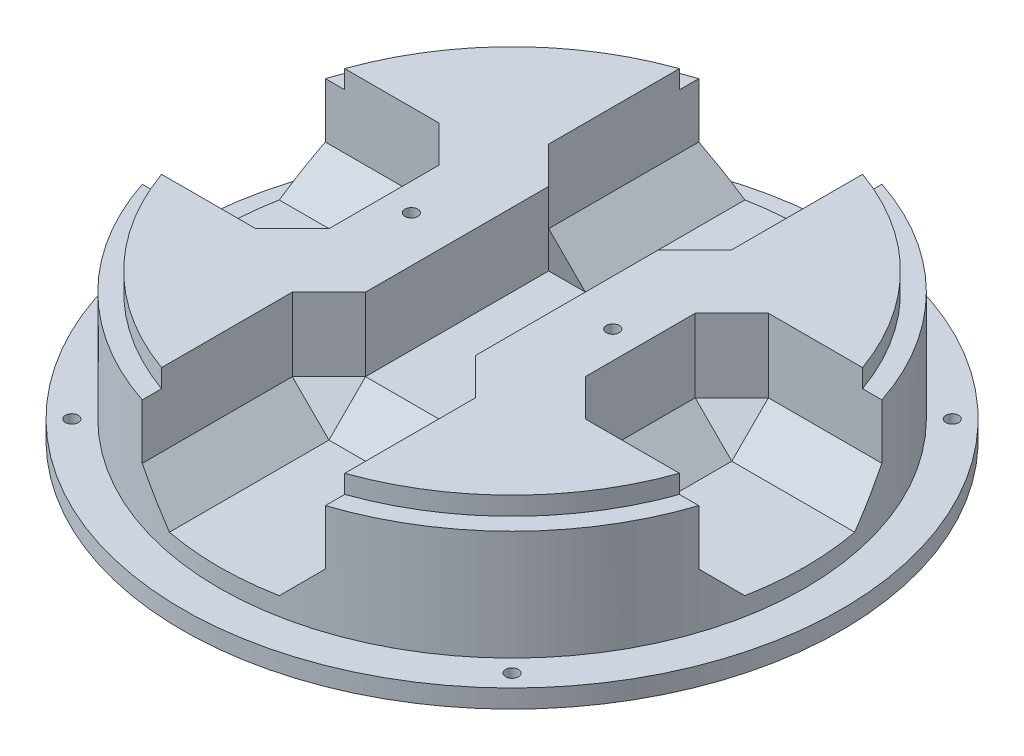
SolidWorks part; units mm, degrees
material "PBT General Purpose"
ref_plane "Front Plane" through (0, 0, 0) normal (0, 0, 1) x (1, 0, 0)
ref_plane "Top Plane" through (0, 0, 0) normal (0, 1, 0) x (1, 0, 0)
ref_plane "Right Plane" through (0, 0, 0) normal (1, 0, 0) x (0, 0, -1)
sketch "Sketch1" plane through (0, 0, 0) normal (0, 1, 0) x (1, 0, 0)
  circle A0 centre (0, 0) radius 80
  dimension "D1" = 160
extrude "Boss-Extrude1" add sketch "Sketch1" along normal blind 30
sketch "Sketch2" plane through (0, 0, 0) normal (0, -1, 0) x (1, 0, 0)
  circle A0 centre (0, 0) radius 90
  dimension "D1" = 180
extrude "Boss-Extrude2" add sketch "Sketch2" along normal blind 5
sketch "Sketch6" plane through (0, 30, 0) normal (0, 1, 0) x (1, 0, 0)
  circle A0 centre (0, 0) radius 75
  dimension "D1" = 150
extrude "Boss-Extrude3" add sketch "Sketch6" along normal blind 5
hole_wizard "Ø3.5 (3.5) Diameter Hole1" positions "Sketch5" profile "Sketch4" hole size "Ø3.5" standard "ISO"
sketch "Sketch5" plane through (-12.746, 35, -7.8689) normal (0, 1, 0) x (1, 0, 0)
  line L0 (-14.754, -7.8689) -> (40.246, -7.8689) construction
  point P1 (-14.754, -7.8689)
  point P2 (40.246, -7.8689)
  dimension "D1" = 55
sketch "Sketch4" plane through (-27.5, 35, 0) normal (1, 0, 0) x (0, 0, 1)
  line L0 (0, 0) -> (0, 11.0515)
  line L1 (0, 11.0515) -> (1.75, 10)
  line L2 (1.75, 10) -> (1.75, 0)
  line L5 (1.75, 0) -> (0, 0)
  line L10 (0, 11.0515) -> (-1.75, 10) construction
  line L11 (0, -6.35) -> (0, 107.95) construction
  dimension "Hole Dia." = 3.5
  dimension "Hole Depth" = 10
  dimension "Drill Angle" = 118
sketch "Sketch7" plane through (0, 35, 0) normal (0, 1, 0) x (1, 0, 0)
  line L0 (0, 25) -> (0, -25) construction
  line L1 (-25, 135) -> (25, 135)
  line L2 (-25, 135) -> (-25, 25)
  line L3 (-25, 25) -> (25, 25)
  line L4 (25, 135) -> (25, 25)
  line L5 (-25, 135) -> (25, 25) construction
  line L6 (-25, 25) -> (25, 135) construction
  line L7 (-25, -25) -> (25, -25)
  line L8 (-25, -25) -> (-25, -135)
  line L9 (-25, -135) -> (25, -135)
  line L10 (25, -25) -> (25, -135)
  line L11 (-25, -25) -> (25, -135) construction
  line L12 (-25, -135) -> (25, -25) construction
  circle A0 centre (0, 0) radius 80 construction
  circle A1 centre (0, 0) radius 80 construction
  point P0 (0, 80)
  point P9 (0, -80)
  dimension "D1" = 50
  dimension "D2" = 50
extrude "Cut-Extrude1" cut sketch "Sketch7" against normal blind 30
chamfer "Chamfer1" distance 10 angle 45 10 edges at (-25, 5, -50.4967) (25, 5, -50.4967) (25, 20, -25) (-25, 20, -25) (0, 5, -25) (-25, 5, 50.4967) (25, 5, 50.4967) (25, 20, 25) (-25, 20, 25) (0, 5, 25)
sketch "Sketch8" plane through (0, 35, 0) normal (0, 1, 0) x (1, 0, 0)
  line L1 (15, 25) -> (-15, 25)
  line L2 (15, 25) -> (15, -25)
  line L3 (15, -25) -> (-15, -25)
  line L4 (-15, 25) -> (-15, -25)
  line L5 (15, 25) -> (-15, -25) construction
  line L6 (15, -25) -> (-15, 25) construction
  point P0 (0, 0)
extrude "Cut-Extrude2" cut sketch "Sketch8" against normal blind 20
hole_wizard "Ø3.5 (3.5) Diameter Hole2" positions "Sketch10" profile "Sketch9" hole size "Ø3.5" standard "ISO"
sketch "Sketch10" plane through (0, 0, 0) normal (0, 1, 0) x (1, 0, 0)
  line L1 (-60.1041, 60.1041) -> (60.1041, 60.1041)
  line L2 (-60.1041, 60.1041) -> (-60.1041, -60.1041)
  line L3 (-60.1041, -60.1041) -> (60.1041, -60.1041)
  line L4 (60.1041, 60.1041) -> (60.1041, -60.1041)
  line L5 (-60.1041, 60.1041) -> (60.1041, -60.1041) construction
  line L6 (-60.1041, -60.1041) -> (60.1041, 60.1041) construction
  point P1 (0, 0)
  point P2 (60.1041, -60.1041)
  point P99 (-60.1041, 60.1041)
  point P100 (-60.1041, -60.1041)
  point P101 (60.1041, 60.1041)
  dimension "D1" = 170
sketch "Sketch9" plane through (0, 0, 0) normal (1, 0, 0) x (0, 0, 1)
  line L0 (0, 0) -> (0, 11.0515)
  line L1 (0, 11.0515) -> (1.75, 10)
  line L2 (1.75, 10) -> (1.75, 0)
  line L5 (1.75, 0) -> (0, 0)
  line L10 (0, 11.0515) -> (-1.75, 10) construction
  line L11 (0, -6.35) -> (0, 107.95) construction
  dimension "Hole Dia." = 3.5
  dimension "Hole Depth" = 10
  dimension "Drill Angle" = 118
sketch "Sketch11" plane through (0, 35, 0) normal (0, 1, 0) x (1, 0, 0)
  line L0 (35, 0) -> (-35, 0) construction
  line L1 (115, -25) -> (35, -25)
  line L2 (115, -25) -> (115, 25)
  line L3 (115, 25) -> (35, 25)
  line L4 (35, -25) -> (35, 25)
  line L5 (115, -25) -> (35, 25) construction
  line L6 (115, 25) -> (35, -25) construction
  line L7 (-35, -25) -> (-115, -25)
  line L8 (-35, -25) -> (-35, 25)
  line L9 (-35, 25) -> (-115, 25)
  line L10 (-115, -25) -> (-115, 25)
  line L11 (-35, -25) -> (-115, 25) construction
  line L12 (-35, 25) -> (-115, -25) construction
  arc A0 (25, -70.7107) -> (25, 70.7107) centre (0, 0) ccw construction
  arc A1 (-25, 70.7107) -> (-25, -70.7107) centre (0, 0) ccw construction
  point P0 (75, 0)
  point P8 (-75, 0)
  dimension "D1" = 50
  dimension "D2" = 70
extrude "Cut-Extrude3" cut sketch "Sketch11" against normal blind 30
chamfer "Chamfer2" distance 10 angle 45 10 edges at (-55.4967, 5, 25) (-35, 20, 25) (-55.4967, 5, -25) (-35, 20, -25) (-35, 5, 0) (55.4967, 5, -25) (35, 20, -25) (35, 5, 0) (35, 20, 25) (55.4967, 5, 25)
